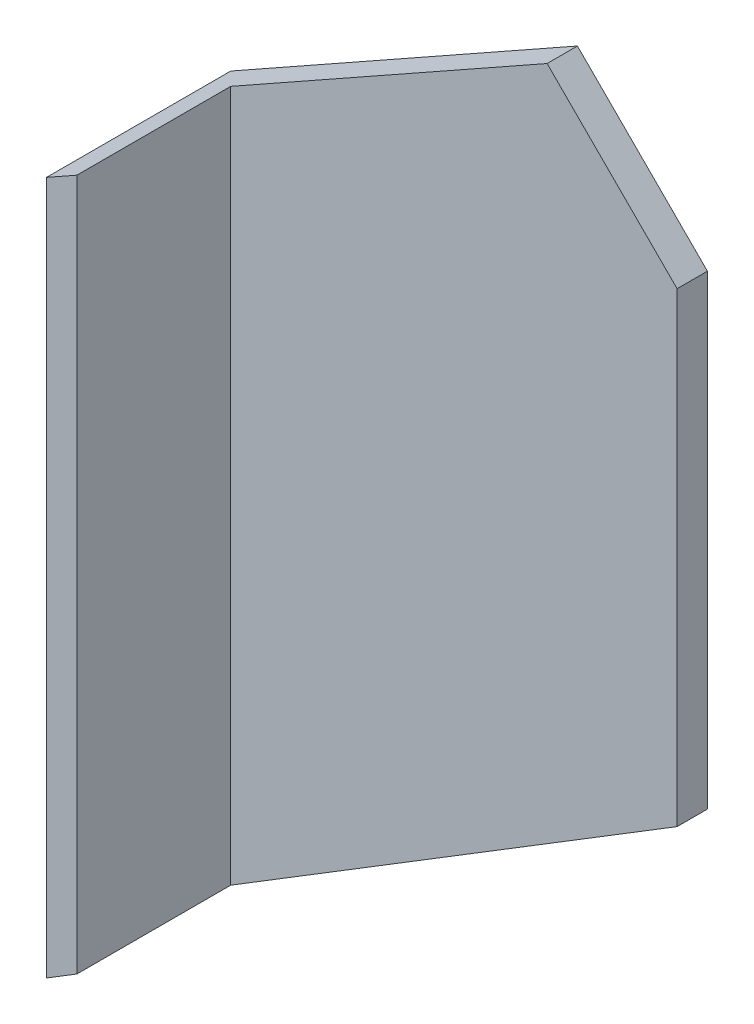
SolidWorks part; units mm, degrees
ref_plane "前视基准面" through (0, 0, 0) normal (0, 0, 1) x (1, 0, 0)
ref_plane "上视基准面" through (0, 0, 0) normal (0, 1, 0) x (1, 0, 0)
ref_plane "右视基准面" through (0, 0, 0) normal (1, 0, 0) x (0, 0, -1)
sketch "草图1" plane through (0, 0, 0) normal (0, 0, 1) x (1, 0, 0)
  line L0 (-1074.6542, -63.3767) -> (48925.3458, -63.3767) construction
  line L1 (-159.1564, -1011.9129) -> (-159.1564, 48988.0871) construction
  line L2 (-119.6564, -63.3767) -> (-119.6564, 256.6233)
  line L3 (-1159.1564, 71.6233) -> (48840.8436, 71.6233) construction
  line L4 (100.3436, 71.6233) -> (100.3436, 286.6233)
  line L5 (40.3436, -1032.1436) -> (40.3436, 48967.8564) construction
  line L6 (-1249.4209, 346.6233) -> (48750.5791, 346.6233) construction
  line L7 (-119.6564, -63.3767) -> (100.3436, 71.6233)
  line L8 (100.3436, 286.6233) -> (40.3436, 346.6233)
  line L9 (40.3436, 346.6233) -> (-119.6564, 256.6233)
  line L10 (1840.8436, -949.9726) -> (1840.8436, 49050.0274) construction
  line L11 (-67.2456, 2321.6233) -> (49932.7544, 2321.6233) construction
  line L12 (1840.8436, 2321.6233) -> (-31377.3484, -35048.8426) construction
  point P21 (-159.1564, 71.6233)
  dimension "D1" = 320
  dimension "D2" = 39.5
  dimension "D3" = 135
  dimension "D4" = 215
  dimension "D5" = 160
  dimension "D6" = 60
  dimension "D7" = 60
  dimension "D8" = 2000
  dimension "D9" = 2250
extrude "凸台-拉伸1" add sketch "草图1" along normal blind 14
sketch "草图3" plane through (0, 0, 14) normal (0, 0, 1) x (1, 0, 0)
  line L0 (-105.6564, 264.4983) -> (-105.6564, -54.7858)
  line L1 (40.3436, 346.6233) -> (-119.6564, 256.6233) construction
  line L2 (-119.6564, -63.3767) -> (100.3436, 71.6233) construction
  line L3 (-119.6564, 256.6233) -> (-119.6564, -63.3767) construction
  line L9 (-119.6564, -63.3767) -> (100.3436, 71.6233)
  line L10 (100.3436, 71.6233) -> (100.3436, 286.6233)
  line L11 (100.3436, 286.6233) -> (40.3436, 346.6233)
  line L12 (40.3436, 346.6233) -> (-119.6564, 256.6233)
  line L13 (-119.6564, 256.6233) -> (-119.6564, -63.3767)
  line L14 (-119.6564, -63.3767) -> (-105.6564, -54.7858)
  line L17 (-105.6564, 264.4983) -> (-119.6564, 256.6233)
  line L18 (-119.6564, 256.6233) -> (-119.6564, -63.3767)
  dimension "D1" = 14
  dimension "D2" = 0
extrude "凸台-拉伸2" add sketch "草图3" along normal blind 71
